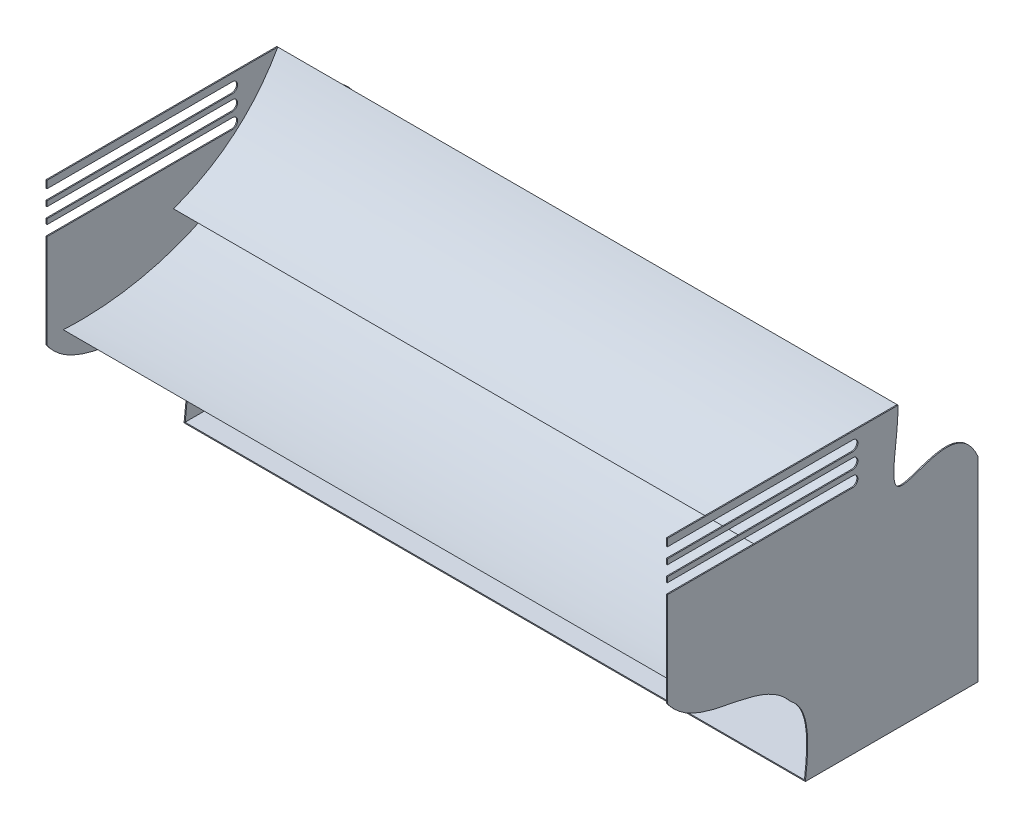
SolidWorks part; units mm, degrees
material "Hexcel AS4C (3000 Filaments)"
ref_plane "Front Plane" through (0, 0, 0) normal (0, 0, 1) x (1, 0, 0)
ref_plane "Top Plane" through (0, 0, 0) normal (0, 1, 0) x (1, 0, 0)
ref_plane "Right Plane" through (0, 0, 0) normal (1, 0, 0) x (0, 0, -1)
sketch "Sketch3" plane through (0, 0, 0) normal (1, 0, 0) x (0, 0, -1)
  line L0 (0, 0) -> (0, 53215.7306) construction
  line L1 (0, 0) -> (1560.3678, 0) construction
  line L2 (566.0212, 618.0336) -> (566.0212, 753.5664) construction
  line L3 (338.5701, 0) -> (762, 0)
  line L4 (0, 216.9745) -> (0, 685.8)
  line L5 (0, 685.8) -> (566.0212, 685.8)
  line L6 (762, 0) -> (762, 478.6438)
  line L7 (591.3318, 510.8493) -> (528.9855, 510.8493) construction
  line L8 (124.7436, 216.9745) -> (-124.7436, 216.9745) construction
  spline S0 degree 3 poles (566.0212, 685.8) (566.0212, 609.5628) (511.0186, 418.0648) (711.566, 596.214) (762, 478.6438) knots 0 0 0 0 0.433377 1 1 1 1
  spline S1 degree 3 poles (0, 216.9745) (268.1536, 216.9745) (370.7959, 243.0789) (338.5701, 0) knots 0 0 0 0 1 1 1 1
  dimension "D1" = 685.8
  dimension "D2" = 762
extrude "Boss-Extrude1" add sketch "Sketch3" against normal blind 2.54 from offset 762
mirror "Mirror1" about plane through (0, 0, 0) normal (1, 0, 0) of bodies 101
sketch "Sketch8" plane through (0, 0, 0) normal (1, 0, 0) x (0, 0, -1)
  spline S0 degree 2 poles (566.0212, 685.8) (478.9461, 530.5926) (310.0418, 470.2609) knots 0 0 0 1 1 1
  spline S1 degree 2 poles (566.0212, 685.8) (535.193, 473.792) (310.0418, 470.2609) knots 0 0 0 1 1 1
  spline S2 degree 2 poles (493.8054, 481.1775) (291.8202, 335.218) (39.8548, 348.3583) knots 0 0 0 1 1 1
  spline S3 degree 2 poles (493.8054, 481.1775) (323.5984, 237.8631) (39.8548, 348.3583) knots 0 0 0 1 1 1
extrude "Boss-Extrude3" add sketch "Sketch8" along normal up to body (759.46 mm away) and the other way through all separate body
sketch "Sketch13" plane through (0, 0, 0) normal (0, 1, 0) x (1, 0, 0)
  line L1 (-762, 338.5701) -> (762, 338.5701)
  line L2 (-762, 338.5701) -> (-762, 762)
  line L3 (-762, 762) -> (762, 762)
  line L4 (762, 338.5701) -> (762, 762)
extrude "Boss-Extrude4" add sketch "Sketch13" along normal blind 2.54 separate body
sketch "Sketch16" plane through (0, 0, 0) normal (1, 0, 0) x (0, 0, -1)
  line L0 (0, 667.6702) -> (454.6874, 667.6702)
  line L1 (0, 685.8) -> (0, 216.9745) construction
  line L2 (0, 642.2702) -> (454.6874, 642.2702)
  line L3 (467.3874, 654.9702) -> (467.3874, -49345.0298) construction
  line L4 (467.3874, 487.2093) -> (-49532.6126, 487.2093) construction
  line L5 (0, 604.1702) -> (454.6874, 604.1702)
  line L6 (0, 629.5702) -> (454.6874, 629.5702)
  line L7 (0, 566.0702) -> (454.6874, 566.0702)
  line L8 (0, 591.4702) -> (454.6874, 591.4702)
  arc A0 (0, 667.6702) -> (0, 642.2702) centre (0, 654.9702) ccw
  arc A1 (454.6874, 667.6702) -> (454.6874, 642.2702) centre (454.6874, 654.9702) cw
  arc A2 (0, 629.5702) -> (0, 604.1702) centre (0, 616.8702) ccw
  arc A3 (0, 591.4702) -> (0, 566.0702) centre (0, 578.7702) ccw
  arc A4 (454.6874, 629.5702) -> (454.6874, 604.1702) centre (454.6874, 616.8702) cw
  arc A5 (454.6874, 591.4702) -> (454.6874, 566.0702) centre (454.6874, 578.7702) cw
  point P10 (467.3874, 654.9702)
  dimension "D1" = 25.4
  dimension "D2" = 3
extrude "Cut-Extrude1" cut sketch "Sketch16" against normal through all both and the other way through all
sketch "Sketch17" plane through (0, 0, 0) normal (1, 0, 0) x (0, 0, -1)
  line L0 (0, 566.0702) -> (0, 216.9745) construction
  line L1 (0, 334.7123) -> (0, 103.6431)
  line L2 (0, 103.6431) -> (302.9996, 187.6548)
  spline S0 degree 3 poles (302.9996, 187.6548) (225.2185, 285.7396) (76.8008, 227.8512) (0, 334.7123) knots 0 0 0 0 1 1 1 1
  spline S1 degree 3 poles (0, 216.9745) (267.216, 216.9745) (370.0761, 242.8967) (338.9032, 2.54) knots 0 0 0 0 0.996503 0.996503 0.996503 0.996503 construction
extrude "Cut-Extrude2" cut sketch "Sketch17" against normal through all both and the other way through all
combine bodies "Combine1" operation type add bodies to combine 108 105 104
scale "Scale1" bodies to scale 108 105 104 scale about origin uniform scaling yes scale factor 0.11
